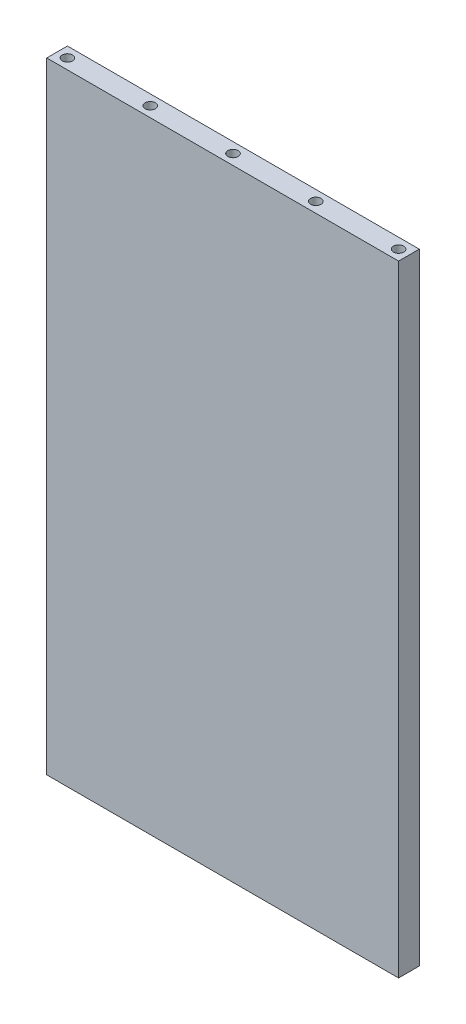
SolidWorks part; units mm, degrees
ref_plane "Alzado" through (0, 0, 0) normal (0, 0, 1) x (1, 0, 0)
ref_plane "Planta" through (0, 0, 0) normal (0, 1, 0) x (1, 0, 0)
ref_plane "Vista lateral" through (0, 0, 0) normal (1, 0, 0) x (0, 0, -1)
sketch "Croquis1" plane through (0, 0, 0) normal (0, 0, 1) x (1, 0, 0)
  line L1 (-85, -150) -> (85, -150)
  line L2 (-85, -150) -> (-85, 150)
  line L3 (-85, 150) -> (85, 150)
  line L4 (85, -150) -> (85, 150)
  line L5 (-85, -150) -> (85, 150) construction
  line L6 (-85, 150) -> (85, -150) construction
  point P1 (0, 0)
  dimension "D1" = 170
  dimension "D2" = 300
extrude "Saliente-Extruir1" add sketch "Croquis1" along normal mid plane 10
sketch "Croquis3" plane through (0, -150, 0) normal (0, -1, 0) x (1, 0, 0)
  line L0 (-85, 0) -> (85, 0) construction
  line L1 (-85, 5) -> (-85, -5) construction
  line L2 (85, 5) -> (85, -5) construction
  line L3 (80, 5) -> (80, -5) construction
  line L4 (-85, 5) -> (85, 5) construction
  line L5 (-85, -5) -> (85, -5) construction
  circle A0 centre (80, 0) radius 2.5
  circle A1 centre (40, 0) radius 2.5
  circle A2 centre (0, 0) radius 2.5
  circle A3 centre (-40, 0) radius 2.5
  circle A4 centre (-80, 0) radius 2.5
  dimension "D2" = 5
  dimension "D1" = 5
extrude "Cortar-Extruir2" cut sketch "Croquis3" against normal blind 5
mirror "Simetría1" about plane through (0, 0, 0) normal (0, 1, 0) of "Cortar-Extruir2"
sketch "Croquis4" plane through (-85, 0, 0) normal (-1, 0, 0) x (0, 0, 1)
  line L0 (-5, 0) -> (5, 0) construction
  line L1 (-5, 150) -> (-5, -150) construction
  line L2 (5, 150) -> (5, -150) construction
  line L3 (-5, 77.5) -> (5, 77.5) construction
  circle A0 centre (0, 0) radius 2.5
  circle A1 centre (0, 77.5) radius 2.5
  circle A2 centre (0, -77.5) radius 2.5
  dimension "D1" = 5
  dimension "D3" = 5
  dimension "D2" = 77.5
extrude "Cortar-Extruir3" cut sketch "Croquis4" against normal blind 5
